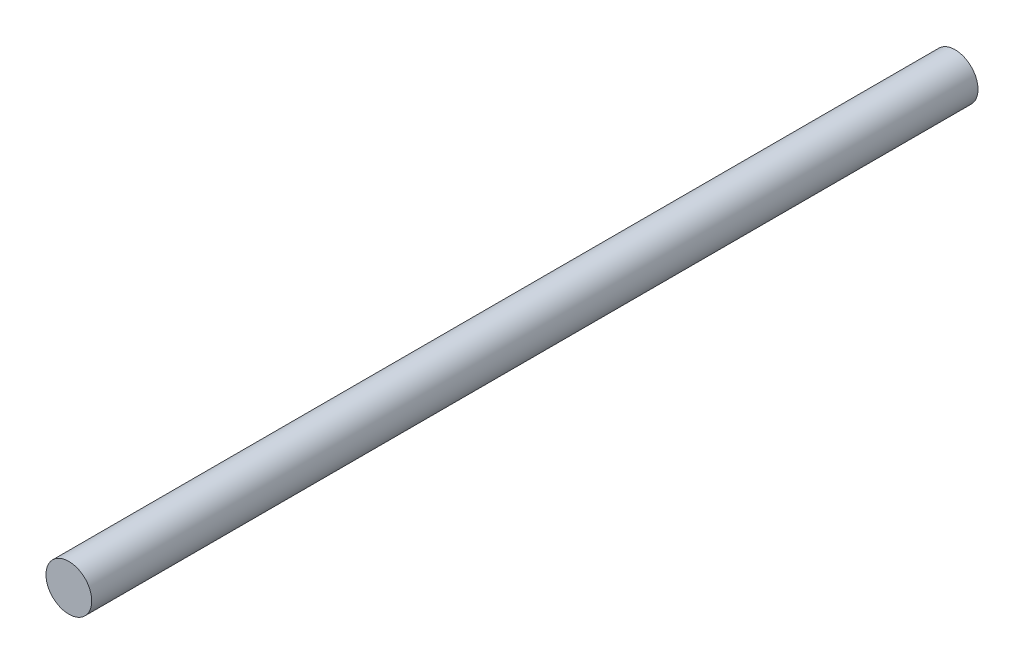
SolidWorks part; units mm, degrees
ref_plane "Alzado" through (0, 0, 0) normal (0, 0, 1) x (1, 0, 0)
ref_plane "Planta" through (0, 0, 0) normal (0, 1, 0) x (1, 0, 0)
ref_plane "Vista lateral" through (0, 0, 0) normal (1, 0, 0) x (0, 0, -1)
sketch "Croquis1" plane through (0, 0, 0) normal (0, 0, 1) x (1, 0, 0)
  circle A0 centre (-44.5589, 16.2139) radius 31
extrude "Saliente-Extruir1" add sketch "Croquis1" along normal blind 1200
